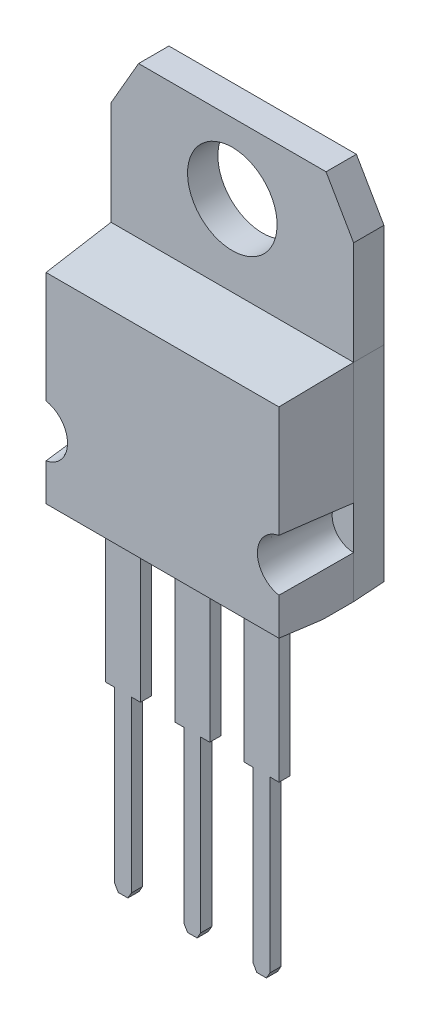
SolidWorks part; units mm, degrees
ref_plane "Front Plane" through (0, 0, 0) normal (0, 0, 1) x (1, 0, 0)
ref_plane "Top Plane" through (0, 0, 0) normal (0, 1, 0) x (1, 0, 0)
ref_plane "Right Plane" through (0, 0, 0) normal (1, 0, 0) x (0, 0, -1)
sketch "Skizze1" plane through (0, 0, 0) normal (0, 0, 1) x (1, 0, 0)
  line L0 (-5.08, -3.385) -> (5.08, -3.385)
  line L1 (5.08, -12.15) -> (-5.08, -12.15)
  line L2 (5.08, -12.15) -> (5.08, 2.95)
  line L3 (5.08, 2.95) -> (-5.08, 2.95)
  line L4 (-5.08, -12.15) -> (-5.08, 2.95)
  line L5 (5.08, -12.15) -> (-5.08, 2.95) construction
  line L6 (5.08, 2.95) -> (-5.08, -12.15) construction
  circle A0 centre (0, 0) radius 1.875
  point P0 (0, -4.6)
  dimension "D1" = 3.75
  dimension "D2" = 10.16
  dimension "D3" = 2.95
  dimension "D4" = 8.765
  dimension "D5" = 15.1
  dimension "D6" = 6.335
extrude "Aufsatz-Linear austragen1" add sketch "Skizze1" along normal blind 4.195 contours L4 L1 L2 L0 | L4 L0 L2 L3 A0
sketch "Skizze3" plane through (0, 0, 0) normal (1, 0, 0) x (0, 0, -1)
  line L0 (-1.27, 2.95) -> (-1.27, -3.385)
  line L1 (-4.195, 2.95) -> (0, 2.95) construction
  line L2 (-1.27, -3.385) -> (-4.195, -3.6409)
  line L3 (-4.195, -12.15) -> (-4.195, 2.95) construction
  line L4 (-4.195, -3.6409) -> (-4.195, -12.0297)
  line L5 (-4.195, -12.0297) -> (-2.475, -12.15)
  line L6 (-4.195, -12.15) -> (0, -12.15) construction
  line L7 (-2.475, -12.15) -> (0, -11.9769)
  line L8 (0, -12.15) -> (0, 2.95) construction
  line L9 (0, -12.15) -> (0, 2.95) construction
  dimension "D1" = 5
  dimension "D2" = 4
  dimension "D3" = 4
  dimension "D4" = 2.475
  dimension "D5" = 1.27
extrude "Schnitt-Linear austragen1" cut sketch "Skizze3" against normal through all both and the other way through all flip side to cut
sketch "Skizze4" plane through (0, 0, 0) normal (0, 1, 0) x (1, 0, 0)
  line L0 (-5.08, -1.27) -> (-4.8755, -4.195)
  line L1 (5.08, -4.195) -> (-5.08, -4.195) construction
  line L2 (5.08, -1.27) -> (4.8755, -4.195)
  line L3 (-4.8755, -4.195) -> (4.8755, -4.195)
  line L4 (0, 0) -> (0, -4.195) construction
  dimension "D1" = 4
extrude "Schnitt-Linear austragen2" cut sketch "Skizze4" against normal through all both and the other way through all
ref_plane "Ebene1" through (0, 0, 2.475) normal (0, 0, 1) x (1, 0, 0)
sketch "Skizze5" plane through (0, 0, 2.475) normal (0, 0, 1) x (1, 0, 0)
  line L0 (-3.63, -11.15) -> (-3.63, -18.5)
  line L1 (-3.63, -18.5) -> (-3.25, -18.5)
  line L2 (-3.25, -18.5) -> (-3.25, -25.6052)
  line L3 (-3.25, -25.6052) -> (-3.1, -25.865)
  line L4 (-3.1, -25.865) -> (-2.7, -25.865)
  line L5 (-2.9, -25.865) -> (-2.9, -11.15) construction
  line L6 (-2.55, -25.6052) -> (-2.7, -25.865)
  line L7 (-2.55, -18.5) -> (-2.55, -25.6052)
  line L8 (-2.17, -18.5) -> (-2.55, -18.5)
  line L9 (-2.17, -11.15) -> (-2.17, -18.5)
  line L10 (-3.63, -11.15) -> (-2.17, -11.15)
  line L11 (5.08, -12.15) -> (-5.08, -12.15) construction
  line L12 (-0.73, -11.15) -> (-0.73, -18.5)
  line L13 (-0.73, -18.5) -> (-0.35, -18.5)
  line L14 (-0.35, -18.5) -> (-0.35, -25.6052)
  line L15 (-0.35, -25.6052) -> (-0.2, -25.865)
  line L16 (-0.2, -25.865) -> (0.2, -25.865)
  line L17 (0.35, -25.6052) -> (0.2, -25.865)
  line L18 (0.35, -18.5) -> (0.35, -25.6052)
  line L19 (0.73, -18.5) -> (0.35, -18.5)
  line L20 (0.73, -11.15) -> (0.73, -18.5)
  line L21 (-0.73, -11.15) -> (0.73, -11.15)
  line L22 (0, -25.865) -> (0, -11.15) construction
  line L23 (2.17, -11.15) -> (2.17, -18.5)
  line L24 (2.17, -18.5) -> (2.55, -18.5)
  line L25 (2.55, -18.5) -> (2.55, -25.6052)
  line L26 (2.55, -25.6052) -> (2.7, -25.865)
  line L27 (2.7, -25.865) -> (3.1, -25.865)
  line L28 (3.25, -25.6052) -> (3.1, -25.865)
  line L29 (3.25, -18.5) -> (3.25, -25.6052)
  line L30 (3.63, -18.5) -> (3.25, -18.5)
  line L31 (3.63, -11.15) -> (3.63, -18.5)
  line L32 (2.17, -11.15) -> (3.63, -11.15)
  line L33 (2.9, -25.865) -> (2.9, -11.15) construction
  dimension "D1" = 1
  dimension "D2" = 6.35
  dimension "D3" = 13.715
  dimension "D4" = 1.46
  dimension "D5" = 0.7
  dimension "D6" = 60
  dimension "D8" = 5.8
  dimension "D9" = 0.4
  dimension "D7" = 3
extrude "Aufsatz-Linear austragen2" add sketch "Skizze5" along normal blind 0.47
sketch "Skizze6" plane through (0, 0, 1.27) normal (0, 0, 1) x (1, 0, 0)
  line L0 (-5.08, -12.15) -> (-5.08, 2.95) construction
  line L1 (0, 0) -> (0, -12.15) construction
  line L2 (5.08, -12.15) -> (-5.08, -12.15) construction
  line L3 (-5.08, -3.385) -> (5.08, -3.385) construction
  circle A0 centre (-5.08, -9.385) radius 0.9
  circle A1 centre (5.08, -9.385) radius 0.9
  dimension "D2" = 1.8
  dimension "D1" = 6
extrude "Schnitt-Linear austragen3" cut sketch "Skizze6" along normal through all draft 4 draft outward yes
chamfer "Fase1" distance 2 angle 30 2 edges at (-5.08, 2.95, 0.635) (5.08, 2.95, 0.635)
sketch "Skizze7" plane through (0, 0, 0) normal (0, 0, 1) x (1, 0, 0)
  line L0 (-5.08, -3.385) -> (5.08, -3.385) construction
  line L1 (-5.08, -3.385) -> (-3.9375, -3.385)
  line L2 (3.9375, -3.385) -> (5.08, -3.385)
  line L3 (3.9253, 2.95) -> (-3.9253, 2.95) construction
  line L4 (3.9375, -3.385) -> (3.9375, -9.845)
  line L5 (3.9375, -9.845) -> (-3.9375, -9.845)
  line L6 (-3.9375, -3.385) -> (-3.9375, -9.845)
  dimension "D1" = 7.875
  dimension "D2" = 12.795
split line "Trennlinie1"
